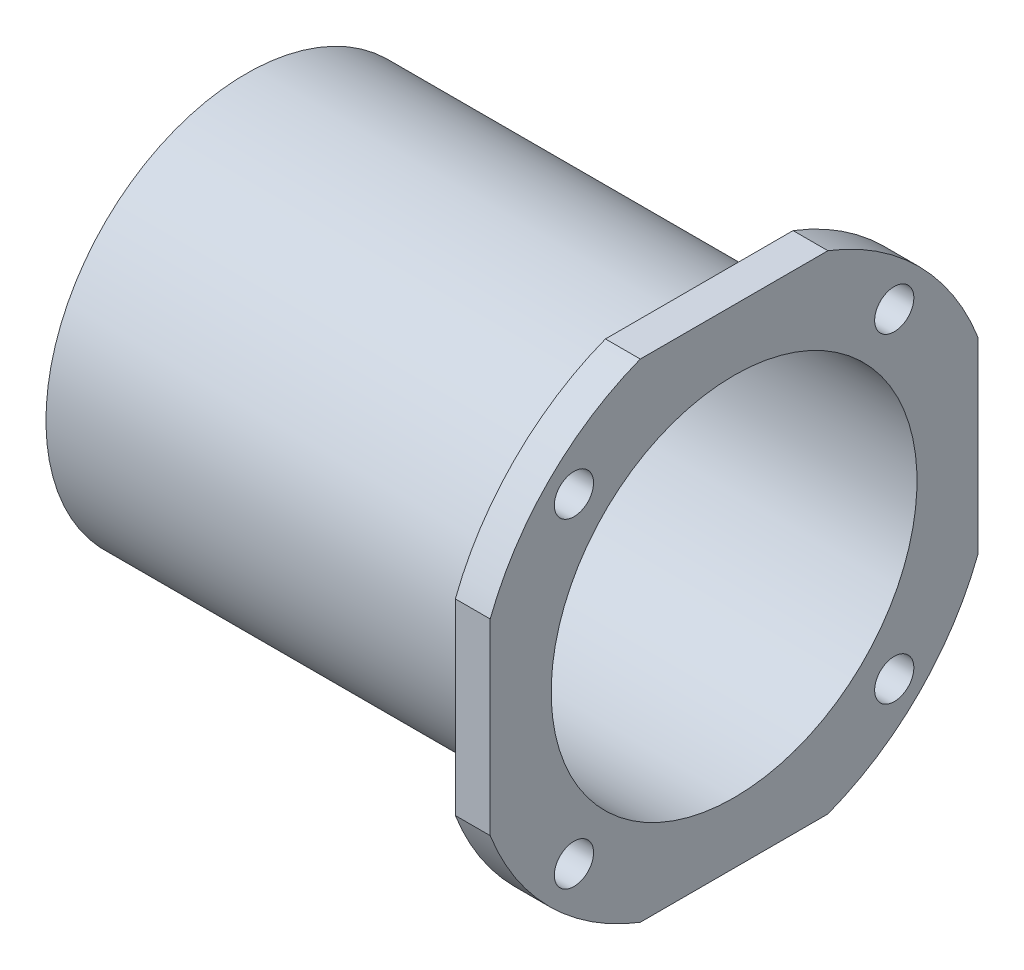
SolidWorks part; units mm, degrees
material "1060 合金"
ref_plane "前视基准面" through (0, 0, 0) normal (0, 0, 1) x (1, 0, 0)
ref_plane "上视基准面" through (0, 0, 0) normal (0, 1, 0) x (1, 0, 0)
ref_plane "右视基准面" through (0, 0, 0) normal (1, 0, 0) x (0, 0, -1)
sketch "草图1" plane through (0, 0, 0) normal (0, 0, 1) x (1, 0, 0)
  line L1 (52, 23) -> (52, 30)
  line L2 (0, 0) -> (20, 0) construction
  line L3 (0, 14) -> (0, 23)
  line L4 (0, 23) -> (52, 23)
  line L5 (56, 21) -> (56, 30)
  line L6 (0, 0) -> (7, 0) construction
  line L7 (52, 30) -> (56, 30)
  line L8 (0, 14) -> (5, 14)
  line L12 (56, 21) -> (5, 21)
  line L13 (5, 14) -> (5, 21)
  dimension "D1" = 21
  dimension "D2" = 14
  dimension "D3" = 2
  dimension "D4" = 4
  dimension "D5" = 5
  dimension "D6" = 52
  dimension "D7" = 7
revolve "旋转2" add sketch "草图1" angle 360 about L2
hole_wizard "打孔尺寸根据十字槽沉头木螺钉的类型2" positions "草图9" profile "草图10" countersink size "M4" standard "GB" end condition through all
sketch "草图9" plane through (0, 0, 0) normal (-1, 0, 0) x (0, 0, 1)
  circle A0 centre (0, 0) radius 17.5 construction
  point P13 (17.5, 0)
  point P14 (0, -17.5)
  point P15 (-17.5, 0)
  point P16 (0, 17.5)
  point P17 (0, 17.5)
  dimension "D1" = 35
sketch "草图10" plane through (0, 0, 17.5) normal (0, 1, 0) x (0, 0, 1)
  line L0 (0, 0) -> (0, 56)
  line L1 (0, 56) -> (2.25, 56)
  line L2 (2.25, 56) -> (2.25, 2.55)
  line L3 (2.25, 2.55) -> (4.3, 0.5)
  line L4 (4.3, 0.5) -> (4.3, 0)
  line L6 (4.3, 0) -> (0, 0)
  line L7 (-2.25, 2.55) -> (-4.3, 0.5) construction
  line L11 (0, -6.35) -> (0, 107.95) construction
  dimension "通孔孔直径" = 4.5
  dimension "通孔孔深度" = 56
  dimension "锥形沉头孔直径" = 8.6
  dimension "锥形沉头孔角度" = 90
  dimension "头间隙" = 0.5
sketch "草图18" plane through (56, 0, 0) normal (1, 0, 0) x (0, 0, -1)
  line L1 (-28, -28) -> (28, -28)
  line L2 (-28, -28) -> (-28, 28)
  line L3 (-28, 28) -> (28, 28)
  line L4 (28, -28) -> (28, 28)
  line L5 (-28, -28) -> (28, 28) construction
  line L6 (-28, 28) -> (28, -28) construction
  point P0 (0, 0)
  dimension "D1" = 56
extrude "切除-拉伸3" cut sketch "草图18" against normal up to surface (4 mm away) flip side to cut up to face at (52, -23, 0)
hole_wizard "M4 间隙孔1" positions "草图22" profile "草图21" hole size "M4" standard "GB" end condition up to next
sketch "草图22" plane through (56, 0, 0) normal (1, 0, 0) x (0, 0, -1)
  line L0 (0, 0) -> (18.3848, 18.3848) construction
  line L3 (0, 0) -> (0, 39.9055) construction
  point P0 (18.3848, 18.3848)
  point P31 (18.3848, -18.3848)
  point P32 (-18.3848, -18.3848)
  point P33 (-18.3848, 18.3848)
  dimension "D1" = 26
  dimension "D2" = 45
  dimension "D3" = 4
sketch "草图21" plane through (56, 18.3848, -18.3848) normal (0, 1, 0) x (0, 0, -1)
  line L0 (0, 0) -> (0, 4)
  line L1 (0, 4) -> (2.25, 4)
  line L2 (2.25, 4) -> (2.25, 0)
  line L5 (2.25, 0) -> (0, 0)
  line L11 (0, -6.35) -> (0, 107.95) construction
  dimension "通孔孔直径" = 4.5
  dimension "通孔孔深度" = 4
